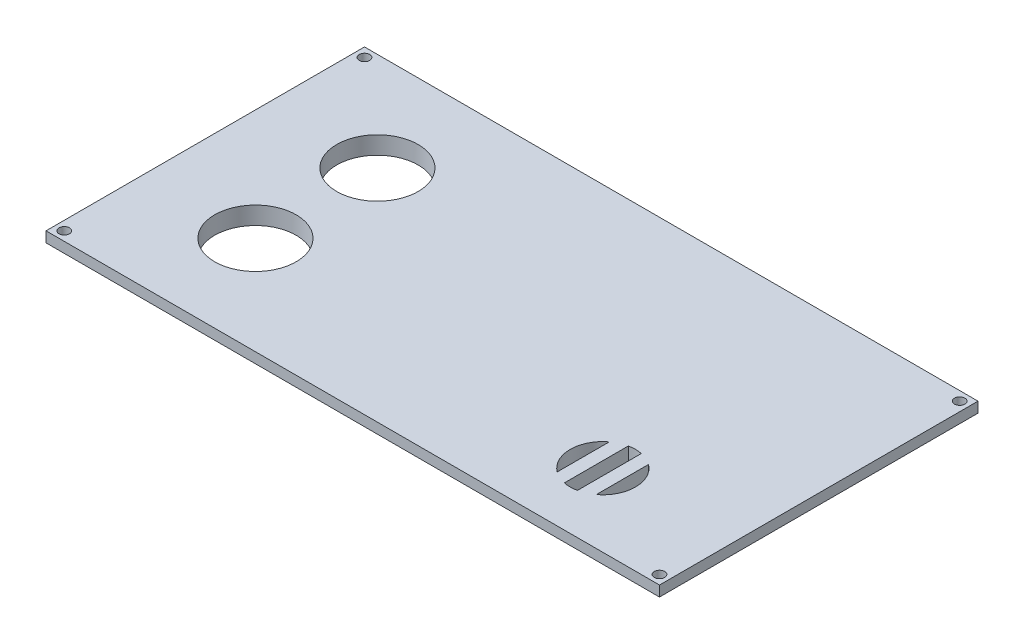
SolidWorks part; units mm, degrees
ref_plane "Plano frontal" through (0, 0, 0) normal (0, 0, 1) x (1, 0, 0)
ref_plane "Plano superior" through (0, 0, 0) normal (0, 1, 0) x (1, 0, 0)
ref_plane "Plano direito" through (0, 0, 0) normal (1, 0, 0) x (0, 0, -1)
sketch "Esboço18" plane through (0, 0, 0) normal (0, 1, 0) x (1, 0, 0)
  line L0 (76.4975, -27.5033) -> (76.4975, 27.4967) construction
  line L1 (76.4975, -27.25) -> (-35.0025, -27.25)
  line L2 (76.4975, -27.25) -> (76.4975, 27.25)
  line L3 (76.4975, 27.25) -> (-35.0025, 27.25)
  line L4 (-35.0025, -27.25) -> (-35.0025, 27.25)
  line L5 (-35.0025, 27.4967) -> (-35.0025, -27.5033) construction
  point P0 (0, 0)
  dimension "D1" = 0
  dimension "D2" = 0
extrude "Ressalto-extrusão2" add sketch "Esboço18" along normal blind 1.4
sketch "Esboço19" plane through (0, 1.4, 0) normal (0, 1, 0) x (1, 0, 0)
  line L0 (79.4975, -30.5033) -> (79.4975, 30.4967) construction
  line L1 (79.4975, -30.5) -> (-38.0025, -30.5)
  line L2 (79.4975, -30.5) -> (79.4975, 30.5)
  line L3 (79.4975, 30.5) -> (-38.0025, 30.5)
  line L4 (-38.0025, -30.5) -> (-38.0025, 30.5)
  line L5 (-38.0025, 30.4967) -> (-38.0025, -30.5033) construction
  line L7 (-38.0025, 30.4967) -> (-38.0025, -30.5033) construction
  point P0 (0, 0)
  dimension "D1" = 0
  dimension "D2" = 0
extrude "Ressalto-extrusão3" add sketch "Esboço19" along normal blind 2
sketch "Esboço24" plane through (0, 3.4, 0) normal (0, 1, 0) x (1, 0, 0)
  line L0 (-38.0025, 30.5) -> (-38.0025, -30.5) construction
  line L1 (79.4975, 30.5) -> (-38.0025, 30.5) construction
  line L2 (-38.0025, -30.5) -> (79.4975, -30.5) construction
  line L3 (79.4975, -30.5) -> (79.4975, 30.5) construction
  circle A0 centre (-36.2525, 28.75) radius 1
  circle A1 centre (77.7475, -28.75) radius 1
  circle A2 centre (-36.25, -28.75) radius 1
  circle A3 centre (77.7475, 28.75) radius 1
  dimension "D1" = 1.75
  dimension "D3" = 1.75
  dimension "D5" = 1.75
  dimension "D2" = 1.75
  dimension "D4" = 1.75
extrude "Corte-extrusão1" cut sketch "Esboço24" against normal through all contours A0 | A3 | A1 | A2
sketch "Esboço25" plane through (0, 7.3114, 0) normal (0, 1, 0) x (1, 0, 0)
  circle A0 centre (-16.6829, 11.6611) radius 7.8
  circle A1 centre (-16.7103, -11.6807) radius 7.8
  circle M2 centre (-16.6829, 11.6611) radius 4.1866
extrude "Corte-extrusão3" cut sketch "Esboço25" against normal through all both and the other way through all contours A0 M2 | M2 | A1
sketch "Esboço26" plane through (0, 0, 0) normal (0, 1, 0) x (1, 0, 0)
  line L0 (79.4975, -24.08) -> (60.9475, -24.08) construction
  line L1 (79.4975, -30.5) -> (79.4975, 30.5) construction
  line L2 (60.9475, -24.08) -> (60.9475, -30.5) construction
  line L3 (-38.0025, -30.5) -> (79.4975, -30.5) construction
  line L4 (60.9475, -24.08) -> (60.9475, -9.02) construction
  line L5 (60.9475, -9.02) -> (47.2875, -9.02) construction
  line L6 (60.9475, -24.08) -> (58.4475, -24.08) construction
  line L7 (58.4475, -11.55) -> (58.4475, -21.55)
  line L10 (55.9475, -10.4263) -> (55.9475, -22.6737)
  line L11 (53.4475, -10.4263) -> (53.4475, -22.6737)
  line L12 (50.9475, -11.55) -> (50.9475, -21.55)
  line L14 (55.9475, -9.02) -> (53.4475, -9.02) construction
  line L15 (48.4475, -16.55) -> (60.9475, -16.55) construction
  line L17 (48.4475, -16.55) -> (48.4475, -24.08) [skipped]
  arc A0 (53.4475, -22.6737) -> (55.9475, -22.6737) centre (54.6975, -16.55) ccw
  arc A1 (50.9475, -11.55) -> (50.9475, -21.55) centre (54.6975, -16.55) ccw
  arc A2 (55.9475, -10.4263) -> (53.4475, -10.4263) centre (54.6975, -16.55) ccw
  arc A3 (58.4475, -21.55) -> (58.4475, -11.55) centre (54.6975, -16.55) ccw
  dimension "D1" = 18.55
  dimension "D2" = 6.42
  dimension "D3" = 15.06
  dimension "D4" = 13.66
  dimension "D5" = 2.5
  dimension "D8" = 2.5
  dimension "D7" = 4
extrude "Corte-extrusão8" cut sketch "Esboço26" along normal through all
